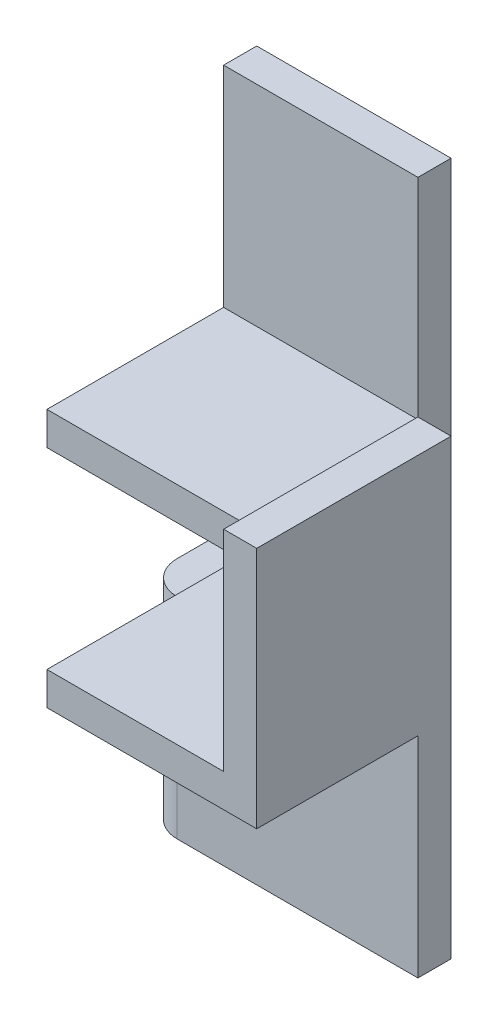
SolidWorks part; units mm, degrees
ref_plane "Front Plane" through (0, 0, 0) normal (0, 0, 1) x (1, 0, 0)
ref_plane "Top Plane" through (0, 0, 0) normal (0, 1, 0) x (1, 0, 0)
ref_plane "Right Plane" through (0, 0, 0) normal (1, 0, 0) x (0, 0, -1)
sketch "Sketch1" plane through (0, 0, 0) normal (0, 1, 0) x (1, 0, 0)
  line L1 (0, 0) -> (22.352, 0)
  line L2 (0, 0) -> (0, -24.13)
  line L3 (0, -24.13) -> (22.352, -24.13)
  line L4 (22.352, 0) -> (22.352, -24.13)
  line L5 (25.908, -27.686) -> (50.038, -27.686)
  line L6 (25.908, -27.686) -> (25.908, -50.038)
  line L7 (25.908, -50.038) -> (50.038, -50.038)
  line L8 (50.038, -27.686) -> (50.038, -50.038)
  dimension "D1" = 22.352
  dimension "D2" = 24.13
  dimension "D3" = 50.038
  dimension "D4" = 24.13
  dimension "D5" = 22.352
  dimension "D6" = 50.038
extrude "Boss-Extrude1" add sketch "Sketch1" along normal blind 3.81 contours L8 L5 L6 L7 | L1 L4 L3 L2
sketch "Sketch2" plane through (0, 3.81, 0) normal (0, 1, 0) x (1, 0, 0)
  line L0 (22.352, 0) -> (22.352, -24.13) construction
  line L1 (0, 0) -> (22.352, 0)
  line L2 (0, 0) -> (0, -3.81)
  line L3 (0, -3.81) -> (22.352, -3.81)
  line L4 (22.352, 0) -> (22.352, -3.81)
  line L5 (25.908, -27.686) -> (50.038, -27.686) construction
  line L6 (50.038, -50.038) -> (46.228, -50.038)
  line L7 (50.038, -50.038) -> (50.038, -27.686)
  line L8 (50.038, -27.686) -> (46.228, -27.686)
  line L9 (46.228, -50.038) -> (46.228, -27.686)
  dimension "D1" = 3.81
  dimension "D2" = 3.81
extrude "Boss-Extrude2" add sketch "Sketch2" along normal blind 24.13
sketch "Sketch3" plane through (0, 0, 0) normal (0, -1, 0) x (1, 0, 0)
  line L0 (22.352, 27.686) -> (50.038, 27.686)
  line L1 (22.352, 0) -> (18.542, 0)
  line L2 (22.352, 0) -> (22.352, 27.686)
  line L4 (18.542, 0) -> (18.542, 31.496)
  line L6 (50.038, 27.686) -> (50.038, 31.496)
  line L7 (50.038, 31.496) -> (18.542, 31.496)
  line L9 (25.908, 27.686) -> (50.038, 27.686) construction
  dimension "D1" = 3.81
  dimension "D2" = 3.81
extrude "Boss-Extrude3" add sketch "Sketch3" along normal blind 24.13
fillet "Fillet1" radius 3.81 1 edges at (18.542, -12.065, 31.496)
